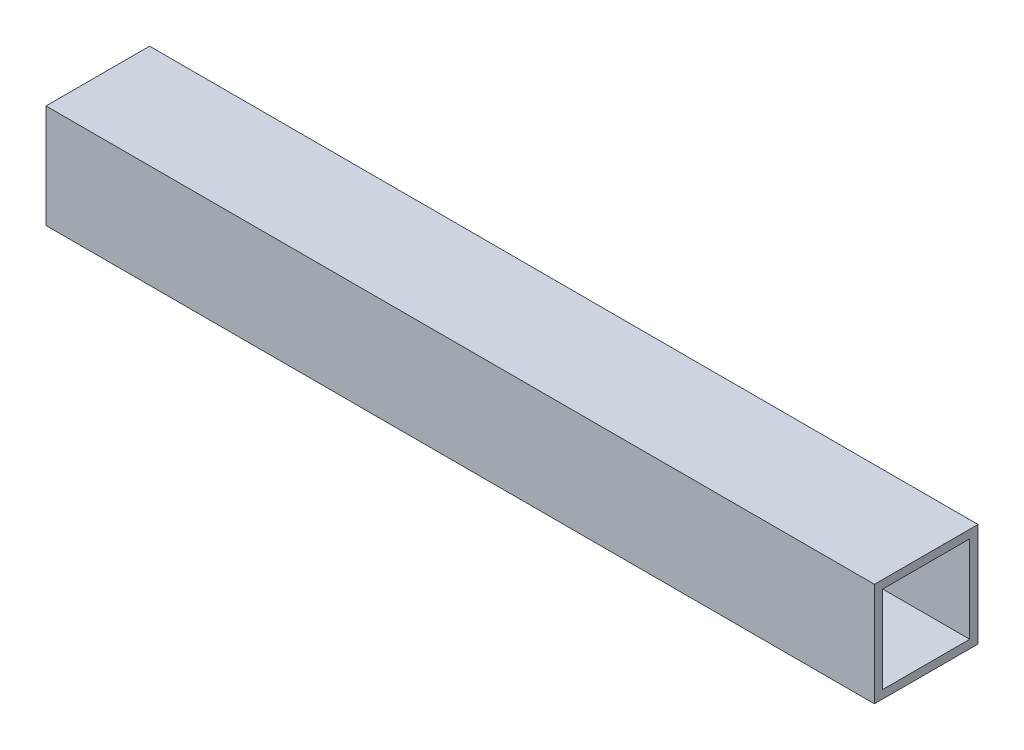
SolidWorks part; units mm, degrees
ref_plane "Front Plane" through (0, 0, 0) normal (1, 0, 0) x (0, 1, 0)
ref_plane "Top Plane" through (0, 0, 0) normal (0, 0, 1) x (0, 1, 0)
ref_plane "Right Plane" through (0, 0, 0) normal (0, 1, 0) x (-1, 0, 0)
sketch "Sketch1" plane through (0, 0, 0) normal (1, 0, 0) x (0, 1, 0)
  line L1 (-160.2509, -28.6327) -> (-122.1509, -28.6327)
  line L2 (-160.2509, -28.6327) -> (-160.2509, 9.4673)
  line L3 (-160.2509, 9.4673) -> (-122.1509, 9.4673)
  line L4 (-122.1509, -28.6327) -> (-122.1509, 9.4673)
  line L5 (-157.2029, 6.4193) -> (-125.1989, 6.4193)
  line L6 (-157.2029, 6.4193) -> (-157.2029, -25.5847)
  line L7 (-157.2029, -25.5847) -> (-125.1989, -25.5847)
  line L8 (-125.1989, 6.4193) -> (-125.1989, -25.5847)
  dimension "D1" = 38.1
  dimension "D2" = 38.1
  dimension "D3" = 3.048
  dimension "D4" = 3.048
  dimension "D5" = 3.048
  dimension "D6" = 3.048
extrude "Boss-Extrude1" add sketch "Sketch1" along normal blind 304.8
